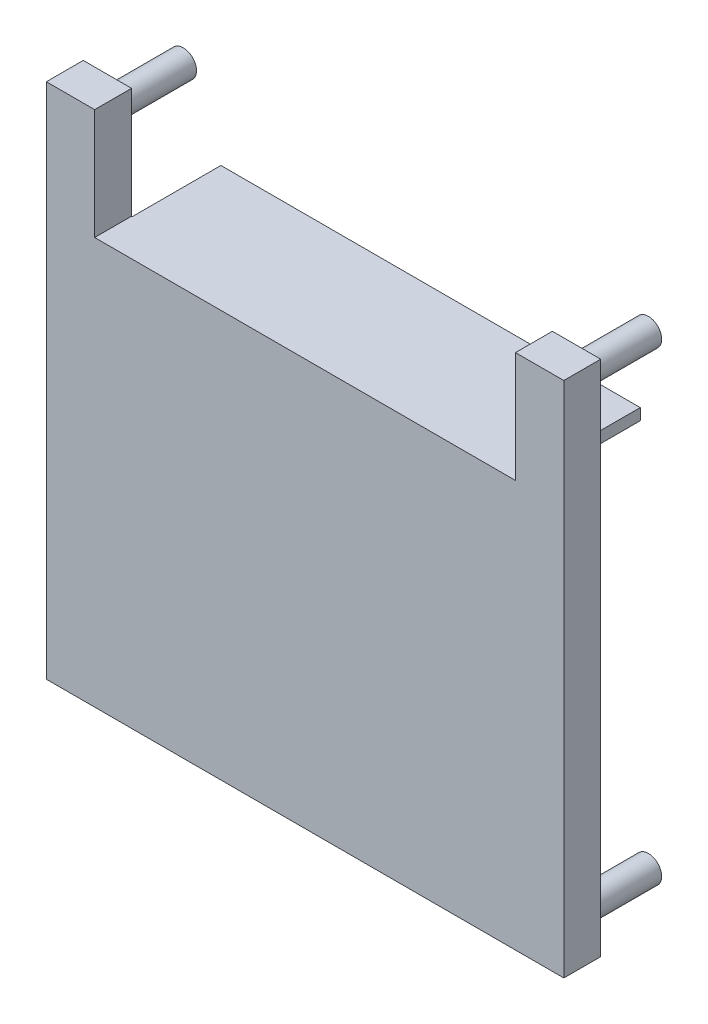
SolidWorks part; units mm, degrees
ref_plane "前视基准面" through (0, 0, 0) normal (0, 0, 1) x (1, 0, 0)
ref_plane "上视基准面" through (0, 0, 0) normal (0, 1, 0) x (1, 0, 0)
ref_plane "右视基准面" through (0, 0, 0) normal (1, 0, 0) x (0, 0, -1)
sketch "草图1" plane through (0, 0, 0) normal (0, 0, 1) x (1, 0, 0)
  line L1 (-35.045, 35.045) -> (35.045, 35.045)
  line L2 (-35.045, 35.045) -> (-35.045, -35.045)
  line L3 (-35.045, -35.045) -> (35.045, -35.045)
  line L4 (35.045, 35.045) -> (35.045, -35.045)
  line L5 (-35.045, 35.045) -> (35.045, -35.045) construction
  line L6 (-35.045, -35.045) -> (35.045, 35.045) construction
  point P0 (0, 0)
extrude "凸台-拉伸1" add sketch "草图1" along normal blind 5
ref_plane "基准面1" through (0, 0, 0) normal (0, 0, 1) x (1, 0, 0)
sketch "草图2" plane through (0, 0, 0) normal (0, 0, 1) x (1, 0, 0)
  circle A0 centre (31.5, 31.5) radius 1.8
  circle A1 centre (31.5, -31.5) radius 1.8
  circle A2 centre (-31.5, -31.5) radius 1.8
  circle A3 centre (-31.5, 31.5) radius 1.8
  point P2 (0, 0)
  point P3 (0, 0)
  point P11 (0, 0)
  dimension "D1" = 4
extrude "凸台-拉伸2" add sketch "草图2" against normal blind 10
ref_plane "基准面3" through (0, 35.045, 0) normal (0, 1, 0) x (1, 0, 0)
sketch "草图4" plane through (0, 35.045, 0) normal (0, 1, 0) x (1, 0, 0)
  line L0 (35.045, -5) -> (-35.045, -5) construction
  line L1 (-28.5, -5) -> (28.5, -5)
  line L2 (-28.5, -5) -> (-28.5, 0)
  line L3 (-28.5, 0) -> (28.5, 0)
  line L4 (28.5, -5) -> (28.5, 0)
extrude "切除-拉伸2" cut sketch "草图4" against normal blind 15
ref_plane "基准面4" through (0, 0, 0) normal (0, 0, -1) x (-1, 0, 0)
sketch "草图5" plane through (0, 0, 0) normal (0, 0, -1) x (-1, 0, 0)
  line L0 (-28.5, 20.045) -> (28.5, 20.045) construction
  line L1 (-28.4, 20.045) -> (28.4, 20.045)
  line L2 (-28.4, 20.045) -> (-28.4, 18.5)
  line L3 (-28.4, 18.5) -> (28.4, 18.5)
  line L4 (28.4, 20.045) -> (28.4, 18.5)
extrude "凸台-拉伸3" add sketch "草图5" along normal blind 12
ref_plane "基准面5" through (0, 0, 0) normal (0, 0, -1) x (-1, 0, 0)
sketch "草图6" plane through (0, 0, 0) normal (0, 0, -1) x (-1, 0, 0)
  line L0 (-28.4, 18.5) -> (28.4, 18.5) construction
  line L1 (-22.5, 0.5) -> (-16.5, 0.5)
  line L2 (-22.5, 0.5) -> (-22.5, 18.5)
  line L3 (-22.5, 18.5) -> (-16.5, 18.5)
  line L4 (-16.5, 0.5) -> (-16.5, 18.5)
extrude "凸台-拉伸4" add sketch "草图6" along normal blind 3.7
sketch "草图7" plane through (0, 0, 0) normal (0, 0, -1) x (-1, 0, 0)
  line L0 (-16.5, 18.5) -> (28.4, 18.5) construction
  line L1 (8, -1.5) -> (23, -1.5)
  line L2 (8, -1.5) -> (8, 18.5)
  line L3 (8, 18.5) -> (23, 18.5)
  line L4 (23, -1.5) -> (23, 18.5)
extrude "凸台-拉伸5" add sketch "草图7" along normal blind 2
